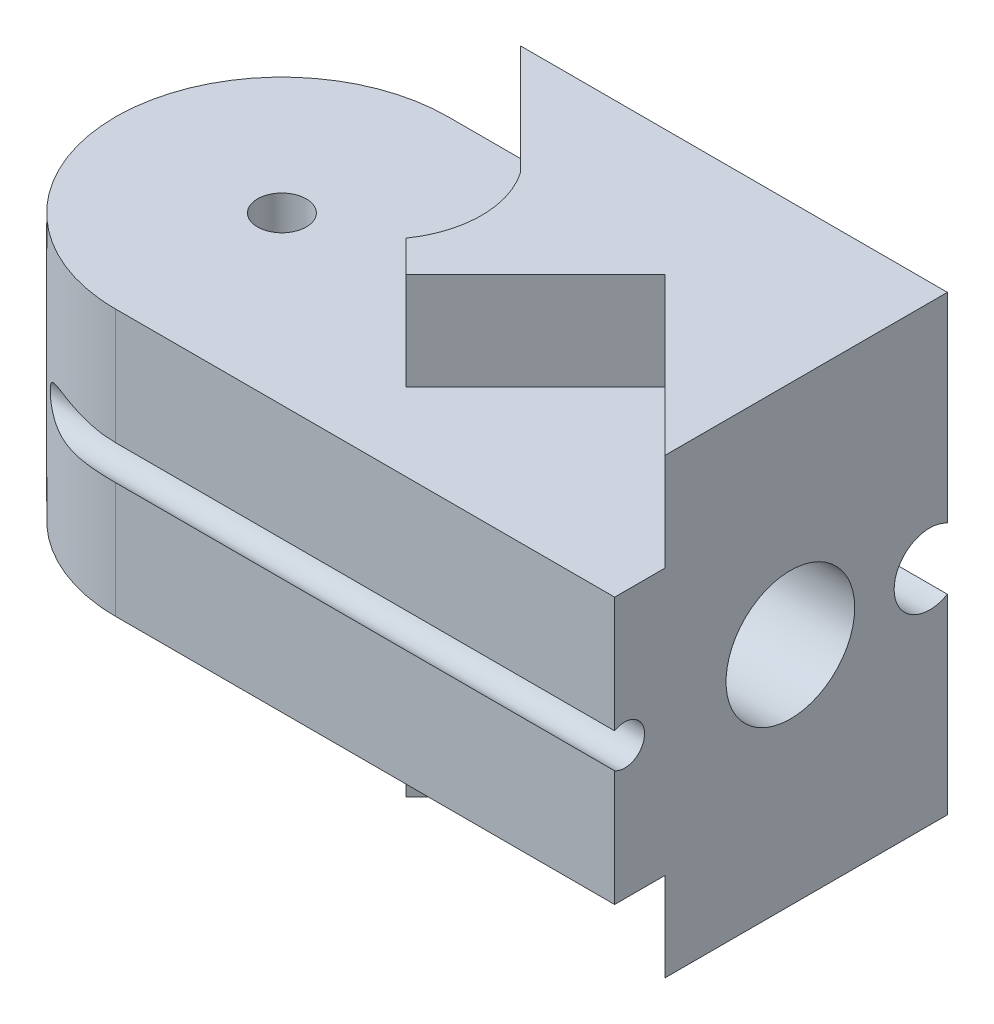
SolidWorks part; units mm, degrees
ref_plane "Front Plane" through (0, 0, 0) normal (0, 0, 1) x (1, 0, 0)
ref_plane "Top Plane" through (0, 0, 0) normal (0, 1, 0) x (1, 0, 0)
ref_plane "Right Plane" through (0, 0, 0) normal (1, 0, 0) x (0, 0, -1)
sketch "Sketch1" plane through (0, 0, 0) normal (0, 1, 0) x (1, 0, 0)
  line L0 (0, 0) -> (15, 0)
  line L1 (15, 0) -> (15, 20)
  line L2 (15, 20) -> (-7.5, 20)
  line L3 (0, 0) -> (0, 5)
  line L4 (0, 5) -> (-7.5, 5)
  line L6 (-7.5, 12.5) -> (-15, 12.5) construction
  line L7 (-7.5, 20) -> (-7.5, 12.5) construction
  ellipse E0 centre (-7.5, 12.5) end of major axis (-7.5, 20) minor radius 7.5 (-15, 12.5) -> (-7.5, 20) cw
  ellipse E1 centre (-7.5, 12.5) end of major axis (0, 12.5) minor radius 7.5 (-15, 12.5) -> (-7.5, 5) ccw
  dimension "D1" = 22.5
  dimension "D2" = 20
  dimension "D3" = 7.5
  dimension "D4" = 7.5
  dimension "D5" = 15
  dimension "D6" = 15
  dimension "D7" = 5
extrude "Boss-Extrude1" add sketch "Sketch1" along normal blind 16
ref_plane "Plane1" through (0, 8, 0) normal (0, 1, 0) x (1, 0, 0)
sketch "Sketch4" plane through (0, 0, 0) normal (0, 1, 0) x (1, 0, 0)
  line L0 (-7.5, 20) -> (-7.5, 12.5) construction
  line L1 (7.9289, 14.3332) -> (2.1004, 8.5047)
  line L2 (2.1004, 8.5047) -> (0.6862, 9.9189)
  line L4 (15, 0) -> (15, 20) construction
  line L7 (0.6862, 15.0811) -> (-4.2327, 20)
  line L8 (15, 20) -> (-7.5, 20) construction
  line L10 (-7.5, 5) -> (0, 5)
  line L11 (0, 5) -> (0, 0)
  line L13 (7.9289, 14.3332) -> (15, 7.2622)
  line L15 (0, 0) -> (15, 0)
  line L16 (15, 0) -> (15, 7.2622)
  line L19 (-7.5, 20) -> (-4.2327, 20)
  circle A0 centre (-7.5, 12.5) radius 7.5 construction
  arc A1 (0.6862, 15.0811) -> (0.6862, 9.9189) centre (-3, 12.5) cw
  ellipse E0 centre (-7.5, 12.5) end of major axis (-15, 12.5) minor radius 7.5 (-7.5, 20) -> (-7.5, 5) ccw
  dimension "D1" = 4.5
  dimension "D2" = 4.5
  dimension "D3" = 70
  dimension "D4" = 45
  dimension "D5" = 2
  dimension "D6" = 10
extrude "Cut-Extrude1" cut sketch "Sketch4" along normal blind 4
ref_plane "Plane2" through (0, 26, 0) normal (0, 1, 0) x (1, 0, 0)
sketch "Sketch5" plane through (0, 26, 0) normal (0, 1, 0) x (1, 0, 0)
  line L20 (7.9289, 14.3332) -> (15, 7.2622)
  line L21 (2.1004, 8.5047) -> (7.9289, 14.3332)
  line L22 (0.6862, 9.9189) -> (2.1004, 8.5047)
  line L23 (-4.2327, 20) -> (0.6862, 15.0811)
  line L24 (15, 20) -> (-4.2327, 20)
  line L25 (15, 7.2622) -> (15, 20)
  line L26 (7.9289, 14.3332) -> (15, 7.2622)
  line L27 (2.1004, 8.5047) -> (7.9289, 14.3332)
  line L28 (0.6862, 9.9189) -> (2.1004, 8.5047)
  line L29 (-4.2327, 20) -> (0.6862, 15.0811)
  line L30 (15, 20) -> (-4.2327, 20)
  line L31 (15, 7.2622) -> (15, 20)
  arc A2 (0.6862, 9.9189) -> (0.6862, 15.0811) centre (-3, 12.5) ccw
  arc A3 (0.6862, 9.9189) -> (0.6862, 15.0811) centre (-3, 12.5) ccw
  dimension "D1" = 0
extrude "Cut-Extrude2" [suppressed] cut sketch "Sketch5" against normal blind 14
sketch "Sketch6" plane through (0, 0, 0) normal (1, 0, 0) x (0, 0, -1)
  line L0 (0, 10) -> (0, 10.5)
  line L1 (0, 16) -> (0, 4) construction
  line L2 (0, 10) -> (0, 5.5)
  line L3 (0, 10.5) -> (4.5941, 10.5)
  line L4 (0, 5.5) -> (4.5941, 5.5)
  line L5 (4.5941, 10.5) -> (4.5941, 5.5)
extrude "Cut-Extrude3" cut sketch "Sketch6" along normal through all
sketch "Sketch7" [suppressed] plane through (0, 8, 0) normal (0, 1, 0) x (1, 0, 0)
  line L0 (7.5, 0) -> (7.5, 2.7594) construction
  line L1 (0, 0) -> (15, 0) construction
  circle A0 centre (7.5, 2.7594) radius 1
extrude "Cut-Extrude4" [suppressed] cut sketch "Sketch7" against normal through all both and the other way through all
sketch "Sketch8" [suppressed] plane through (0, 8, 0) normal (0, 1, 0) x (1, 0, 0)
  line L0 (-7.5, 20) -> (-7.36, 12.5013) construction
  circle A0 centre (-7.36, 12.5013) radius 1.1
extrude "Cut-Extrude5" [suppressed] cut sketch "Sketch8" against normal through all both and the other way through all
fillet "Fillet2" [suppressed] radius 0.5
fillet "Fillet3" [suppressed] radius 0.5
sketch "Sketch9" [suppressed] plane through (0, 8, 0) normal (0, 1, 0) x (1, 0, 0)
  line L0 (0, 5) -> (3.9965, 5) construction
  line L1 (0, 0) -> (15, 0) construction
  line L2 (0, 5) -> (0, 0)
  line L3 (0, 0) -> (3.9965, 0)
  ellipse E0 centre (3.9965, 5) end of major axis (3.9965, 0) minor radius 3.9965 (3.9965, 0) -> (0, 5) cw
extrude "Cut-Extrude6" [suppressed] cut sketch "Sketch9" against normal through all both and the other way through all
fillet "Fillet4" [suppressed] radius 0.5
sketch "Sketch10" [suppressed] plane through (0, 8, 0) normal (0, 1, 0) x (1, 0, 0)
  line L0 (-14.36, 12.5013) -> (-15, 12.5) construction
  line L1 (-7.5, 12.5) -> (-7.5, 19.5) construction
  line L2 (-7.36, 12.5013) -> (-14.36, 12.5013) construction
  line L3 (-7.5, 20) -> (-7.5, 19.4989)
  line L4 (-7.5, 5.5011) -> (-7.5, 5)
  ellipse E0 centre (-7.5, 12.5) end of major axis (-7.4987, 19.4989) minor radius 6.86 (-7.5, 19.4989) -> (-7.5, 5.5011) ccw
  ellipse E1 centre (-7.5, 12.5) end of major axis (-15, 12.5) minor radius 7.5 (-7.5, 20) -> (-7.5, 5) ccw
extrude "Cut-Extrude7" [suppressed] cut sketch "Sketch10" against normal mid plane 1
chamfer "Chamfer1" [suppressed] distance 1 angle 75
chamfer "Chamfer2" [suppressed] distance 1.75 angle 15
scale "Scale1" [suppressed]
ref_plane "symmetry_plane" [suppressed] through (0, 8.75, 0) normal (0, 1, 0) x (1, 0, 0)
sketch "Sketch11" [suppressed] plane through (0, 4.35, 0) normal (0, -1, 0) x (1, 0, 0)
  line L0 (0, -5) -> (15, -5)
  line L1 (0, -5) -> (0, 0.0084)
  line L2 (15, -5) -> (15, 0.0084)
  line L3 (0, 0.0084) -> (15, 0.0084)
  line L4 (15, 0) -> (15, -7.2622) construction
extrude "Cut-Extrude8" [suppressed] cut sketch "Sketch11" against normal through all both and the other way through all
ref_plane "mirror_plane" through (0, 10, 0) normal (0, -1, 0) x (-1, 0, 0)
sketch "Sketch12" plane through (0, 16, 0) normal (0, 1, 0) x (1, 0, 0)
  line L18 (7.9289, 14.3332) -> (15, 7.2622)
  line L19 (2.1004, 8.5047) -> (7.9289, 14.3332)
  line L20 (0.6862, 9.9189) -> (2.1004, 8.5047)
  line L21 (-4.2327, 20) -> (0.6862, 15.0811)
  line L22 (15, 20) -> (-4.2327, 20)
  line L23 (15, 7.2622) -> (15, 20)
  line L24 (7.9289, 14.3332) -> (15, 7.2622)
  line L25 (2.1004, 8.5047) -> (7.9289, 14.3332)
  line L26 (0.6862, 9.9189) -> (2.1004, 8.5047)
  line L27 (-4.2327, 20) -> (0.6862, 15.0811)
  line L28 (15, 20) -> (-4.2327, 20)
  line L29 (15, 7.2622) -> (15, 20)
  arc A3 (0.6862, 9.9189) -> (0.6862, 15.0811) centre (-3, 12.5) ccw
  arc A4 (0.6862, 9.9189) -> (0.6862, 15.0811) centre (-3, 12.5) ccw
  dimension "D1" = 0
extrude "Boss-Extrude2" add sketch "Sketch12" along normal blind 4.4
sketch "Sketch13" plane through (0, 0, 0) normal (-1, 0, 0) x (0, 0, 1)
  line L8 (0, 5.5) -> (-4.5941, 5.5)
  line L9 (-4.5941, 5.5) -> (-4.5941, 10.5)
  line L10 (-4.5941, 10.5) -> (0, 10.5)
  line L11 (0, 10.5) -> (0, 16)
  line L12 (0, 16) -> (-5, 16)
  line L13 (-5, 16) -> (-5, 4)
  line L14 (-5, 4) -> (0, 4)
  line L15 (0, 4) -> (0, 5.5)
  line L16 (0, 5.5) -> (-4.5941, 5.5)
  line L17 (-4.5941, 5.5) -> (-4.5941, 10.5)
  line L18 (-4.5941, 10.5) -> (0, 10.5)
  line L19 (0, 10.5) -> (0, 16)
  line L20 (0, 16) -> (-5, 16)
  line L21 (-5, 16) -> (-5, 4)
  line L22 (-5, 4) -> (0, 4)
  line L23 (0, 4) -> (0, 5.5)
  dimension "D1" = 0
extrude "Cut-Extrude9" cut sketch "Sketch13" against normal through all both and the other way through all
sketch "Sketch14" plane through (0, 4, 0) normal (0, -1, 0) x (1, 0, 0)
  line L0 (-7.5, -5) -> (-7.5, -20)
  line L1 (-7.5, -20) -> (-7.5, -12.5)
  circle A0 centre (-7.5, -12.5) radius 1.1
  dimension "D1" = 2.2
extrude "Cut-Extrude10" cut sketch "Sketch14" against normal through all both and the other way through all contours L0 A0 | L0 A0
ref_point "Point1"
sketch "Sketch15" plane through (15, 0, 0) normal (1, 0, 0) x (0, 0, -1)
  circle A0 centre (12.9217, 10.1811) radius 2.9
  dimension "D1" = 5.8
extrude "ruthex_m3_hole" cut sketch "Sketch15" against normal blind 8.3
fillet "Fillet5" [suppressed] radius 0.5
fillet "Fillet6" [suppressed] radius 2
sketch "Sketch16" plane through (15, 0, 0) normal (1, 0, 0) x (0, 0, -1)
  line L0 (5, 10) -> (20, 10) construction
  line L8 (7.2622, 16) -> (5, 16)
  line L9 (7.2622, 16) -> (5, 16)
  line L10 (20, 0) -> (20, 20.4)
  line L11 (5, 4) -> (7.2622, 4)
  line L12 (5, 4) -> (7.2622, 4)
  line L13 (7.2622, 4) -> (7.2622, 0)
  line L14 (5, 16) -> (5, 4)
  line L15 (7.2622, 4) -> (7.2622, 0)
  line L18 (20, 0) -> (20, 20.4)
  line L22 (5, 16) -> (5, 4)
  line L25 (7.2622, 0) -> (20, 0)
  line L26 (7.2622, 0) -> (20, 0)
  line L27 (20, 20.4) -> (7.2622, 20.4)
  line L28 (20, 20.4) -> (7.2622, 20.4)
  line L29 (7.2622, 20.4) -> (7.2622, 16)
  line L30 (7.2622, 20.4) -> (7.2622, 16)
  arc A0 (5, 10.7794) -> (5, 9.2206) centre (5.45, 10) cw
  arc A1 (20, 11.3856) -> (20, 8.6144) centre (19.2, 10) ccw
  line M14 (20, 0) -> (20, 20.4)
  line M19 (5, 16) -> (5, 4)
  dimension "D2" = 0.9
  dimension "D4" = 1.6
  dimension "D3" = 120
  dimension "D5" = 120
  dimension "D1" = 0
extrude "1.6mm_PTFE_tube_clamp_cutout" cut sketch "Sketch16" against normal through all contours L0 A0 M19 | L22 L0 A0 | A1 L0 M14 | L0 A1 L18
ref_plane "mirror_plane_1" through (0, 0, -12.5) normal (0, 0, -1) x (-1, 0, 0)
